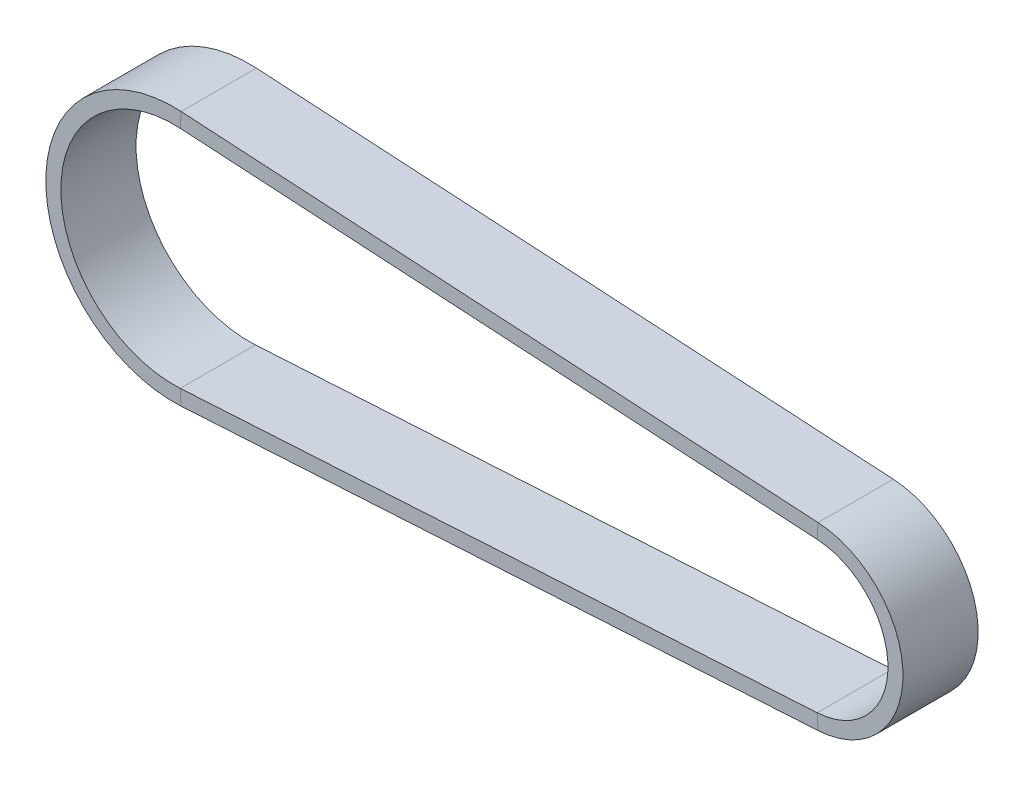
SolidWorks part; units mm, degrees
ref_plane "Ebene vorne" through (0, 0, 0) normal (0, 0, 1) x (1, 0, 0)
ref_plane "Ebene oben" through (0, 0, 0) normal (0, 1, 0) x (1, 0, 0)
ref_plane "Ebene rechts" through (0, 0, 0) normal (1, 0, 0) x (0, 0, -1)
sketch "Skizze2" plane through (0, 0, 0) normal (0, 1, 0) x (1, 0, 0)
  line L0 (-15, -20.5) -> (-17, -20.5) construction
  line L1 (-17, -10.5) -> (-17, -20.5) construction
  line L2 (-15, -10.5) -> (-17, -10.5) construction
  line L3 (-15, -10.5) -> (-15, -20.5) construction
  line L4 (-15, -20.5) -> (-17, -20.5)
  line L5 (-17, -10.5) -> (-17, -20.5)
  line L6 (-15, -10.5) -> (-17, -10.5)
  line L7 (-15, -10.5) -> (-15, -20.5)
ref_plane "Ebene1" through (0, 0, 15.5) normal (0, 0, 1) x (1, 0, 0)
sketch "Skizze3" plane through (0, 0, 15.5) normal (0, 0, 1) x (1, 0, 0)
  line L1 (0, 0) -> (-25, 0) construction
  line L2 (0, 0) -> (450, 0) construction
  line L3 (0.8824, 14.974) -> (85.5882, 9.9827)
  arc A1 (-15, 0) -> (0.8824, 14.974) centre (0, 0) cw
  arc A3 (95, 0) -> (85.5882, 9.9827) centre (85, 0) ccw
  dimension "D1" = 10
  dimension "D2" = 15
sweep "Austragung1" add profiles "Skizze2" path "Skizze3"
mirror "Spiegeln1" about plane through (0, 0, 0) normal (0, -1, 0) of bodies 101
